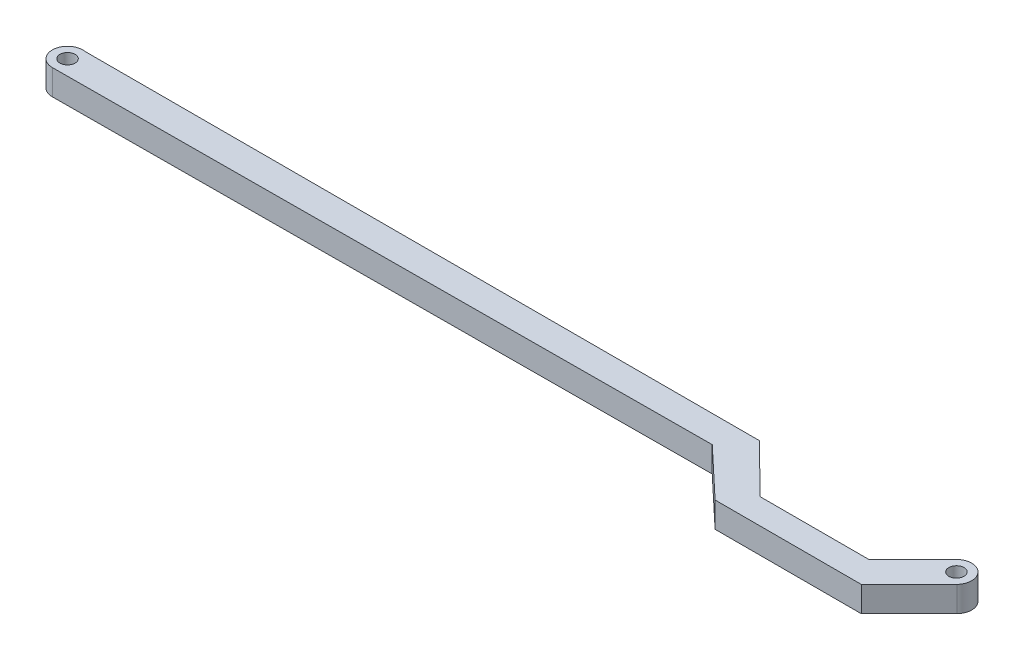
SolidWorks part; units mm, degrees
ref_plane "Alzado" through (0, 0, 0) normal (0, 0, 1) x (1, 0, 0)
ref_plane "Planta" through (0, 0, 0) normal (0, 1, 0) x (1, 0, 0)
ref_plane "Vista lateral" through (0, 0, 0) normal (1, 0, 0) x (0, 0, -1)
sketch "Croquis1" plane through (0, 0, 0) normal (0, 1, 0) x (1, 0, 0)
  line L1 (0, -3) -> (129.2611, -2.3369)
  line L2 (177.151, -2.0912) -> (167.7604, -11.4944)
  line L3 (167.7604, -11.4944) -> (138.9791, -11.4944)
  line L4 (138.9791, -11.4944) -> (129.2611, -2.3369)
  line L5 (133.1978, 2.9911) -> (142.8595, -6.4944)
  line L6 (142.8595, -6.4944) -> (164.2644, -6.4944)
  line L7 (164.2644, -6.4944) -> (172.6101, 1.8135)
  line L9 (133.1978, 2.9911) -> (0.4709, 2.9628)
  circle A0 centre (0, 0) radius 1.5
  circle A1 centre (175, 0) radius 1.5
  arc A2 (177.151, -2.0912) -> (172.6101, 1.8135) centre (175, 0) ccw
  arc A3 (0.4709, 2.9628) -> (0, -3) centre (0, 0) ccw
  dimension "D1" = 3
  dimension "D2" = 3
  dimension "D4" = 6
  dimension "D5" = 6
  dimension "D3" = 175
  dimension "D6" = 5
extrude "Saliente-Extruir1" add sketch "Croquis1" along normal blind 5
